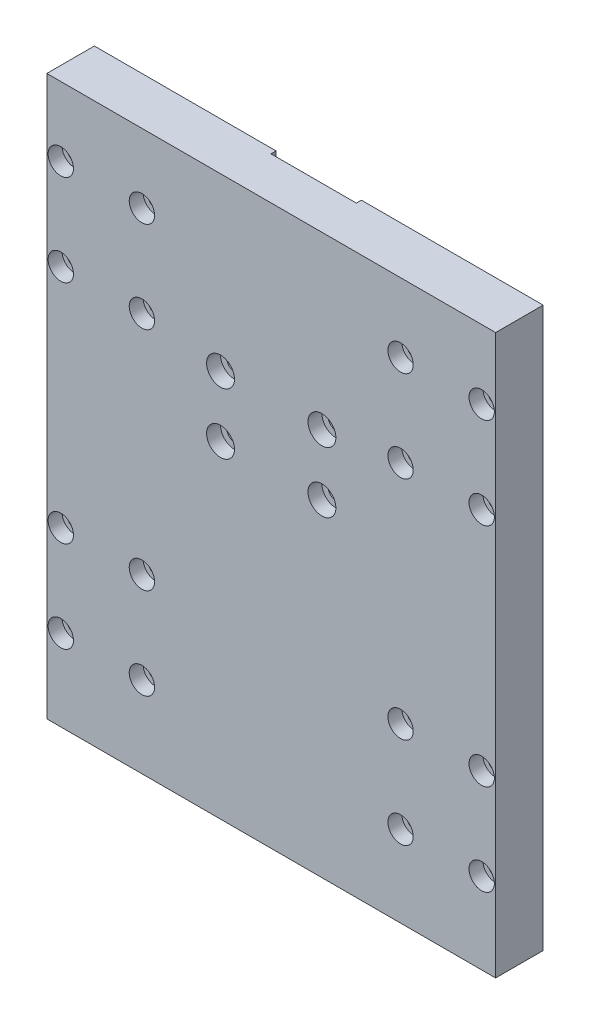
SolidWorks part; units mm, degrees
ref_plane "Front Plane" through (0, 0, 0) normal (0, 0, 1) x (1, 0, 0)
ref_plane "Top Plane" through (0, 0, 0) normal (0, 1, 0) x (1, 0, 0)
ref_plane "Right Plane" through (0, 0, 0) normal (1, 0, 0) x (0, 0, -1)
sketch "Sketch1" plane through (0, 0, 0) normal (0, 0, 1) x (1, 0, 0)
  line L0 (88.5186, 66.4333) -> (-88.5186, 66.4333)
  line L1 (88.5186, 46.4333) -> (88.5186, -4.0667)
  line L3 (88.5186, 46.4333) -> (88.5186, 66.4333)
  line L4 (88.5186, -4.0667) -> (88.5186, -154.0667)
  line L5 (-88.5186, -4.0667) -> (-88.5186, -154.0667)
  line L6 (-88.5186, 46.4333) -> (-88.5186, 66.4333)
  line L7 (-88.5186, 46.4333) -> (-88.5186, -4.0667)
  line L8 (-88.5186, -154.0667) -> (88.5186, -154.0667)
  circle A0 centre (83.0186, 39.1833) radius 3
  circle A1 centre (51.0186, 39.1833) radius 3
  circle A2 centre (83.0186, 3.1833) radius 3
  circle A3 centre (51.0186, 3.1833) radius 3
  circle A4 centre (83.0186, -86.0167) radius 3
  circle A5 centre (51.0186, -86.0167) radius 3
  circle A6 centre (51.0186, -122.0167) radius 3
  circle A7 centre (83.0186, -122.0167) radius 3
  circle A8 centre (-83.0186, -122.0167) radius 3
  circle A9 centre (-51.0186, -122.0167) radius 3
  circle A10 centre (-51.0186, -86.0167) radius 3
  circle A11 centre (-83.0186, -86.0167) radius 3
  circle A12 centre (-51.0186, 3.1833) radius 3
  circle A13 centre (-83.0186, 3.1833) radius 3
  circle A14 centre (-51.0186, 39.1833) radius 3
  circle A15 centre (-83.0186, 39.1833) radius 3
  point P5 (0, 0)
  point P6 (0, 0)
  point P7 (0, 0)
  point P9 (0, 0)
  point P44 (0, 0)
extrude "Boss-Extrude1" add sketch "Sketch1" along normal blind 18.75
sketch "Sketch2" plane through (0, 0, 18.75) normal (0, 0, 1) x (1, 0, 0)
  circle A1 centre (-51.0186, 39.1833) radius 5
  circle A2 centre (-83.0186, 39.1833) radius 5
  circle A3 centre (-83.0186, 3.1833) radius 5
  circle A4 centre (51.0186, 39.1833) radius 5
  circle A5 centre (83.0186, 39.1833) radius 5
  circle A6 centre (83.0186, 3.1833) radius 5
  circle A7 centre (51.0186, 3.1833) radius 5
  circle A8 centre (-51.0186, 3.1833) radius 5
  circle A9 centre (-83.0186, -86.0167) radius 5
  circle A10 centre (-51.0186, -86.0167) radius 5
  circle A11 centre (-51.0186, -122.0167) radius 5
  circle A12 centre (-83.0186, -122.0167) radius 5
  circle A13 centre (51.0186, -122.0167) radius 5
  circle A14 centre (51.0186, -86.0167) radius 5
  circle A15 centre (83.0186, -86.0167) radius 5
  circle A16 centre (83.0186, -122.0167) radius 5
extrude "Cut-Extrude3" cut sketch "Sketch2" against normal blind 5.5
sketch "Sketch4" plane through (0, 0, 18.75) normal (0, 0, 1) x (1, 0, 0)
  circle A0 centre (-20, -25) radius 3
  circle A1 centre (20, -25) radius 3
  circle A2 centre (20, -1) radius 3
  circle A3 centre (-20, -1) radius 3
  dimension "D1" = 2
  dimension "D2" = 2
hole_wizard "CBORE for M5 Hex Head Bolt1" positions "Sketch5" profile "Sketch6" counterbore size "M5" standard "ISO" end condition through all
sketch "Sketch5" plane through (0, 0, 18.75) normal (0, 0, 1) x (1, 0, 0)
  point P0 (-20, -1)
  point P3 (20, -1)
  point P6 (-20, -25)
  point P9 (20, -25)
sketch "Sketch6" plane through (-20, -1, 18.75) normal (1, 0, 0) x (0, -1, 0)
  line L0 (0, 0) -> (0, 18.75)
  line L1 (0, 18.75) -> (3, 18.75)
  line L3 (3, 18.75) -> (3, 5.5)
  line L4 (3, 5.5) -> (5.5, 5.5)
  line L5 (5.5, 5.5) -> (5.5, 0)
  line L7 (5.5, 0) -> (0, 0)
  line L11 (0, -6.35) -> (0, 107.95) construction
  dimension "Thru Hole Dia." = 6
  dimension "Thru Hole Depth" = 18.75
  dimension "C'Bore Dia." = 11
  dimension "C'Bore Depth" = 5.5
sketch "Sketch7" plane through (0, 66.4333, 0) normal (0, 1, 0) x (1, 0, 0)
  line L5 (-14.8284, -2) -> (-16.8284, -2)
  line L6 (-16.8284, -2) -> (-16.8284, 0)
  line L10 (14.8284, -2) -> (16.8284, -2)
  line L12 (-14.8284, -2) -> (14.8284, -2)
  line L14 (16.8284, -2) -> (16.8284, 0)
  line L15 (16.8284, 0) -> (-16.8284, 0)
extrude "Cut-Extrude4" cut sketch "Sketch7" against normal blind 40
sketch "Sketch8" plane through (0, 0, 0) normal (0, 0, -1) x (-1, 0, 0)
  line L0 (18.9411, 17.5285) -> (18.9411, 6.4715)
  line L1 (16.9411, 16.5) -> (16.9411, 7.5)
  line L2 (-16.9411, 7.5) -> (-16.9411, 16.5)
  line L3 (-18.9411, 6.4715) -> (-18.9411, 17.5285)
  line L4 (-17.3614, 5.3543) -> (17.3614, 5.3543)
  line L5 (-17.3614, 18.6457) -> (17.3614, 18.6457)
  arc A0 (18.9411, 17.5285) -> (17.3614, 18.6457) centre (-31.5511, -52.1871) ccw
  arc A1 (-16.225, 17) -> (-16.9411, 16.5) centre (31.551, -52.1869) ccw
  arc A2 (16.9411, 16.5) -> (16.225, 17) centre (-31.5511, -52.1871) ccw
  arc A3 (16.225, 7) -> (16.9411, 7.5) centre (-31.551, 76.1869) ccw
  arc A4 (-16.9411, 7.5) -> (-16.225, 7) centre (31.5511, 76.1871) ccw
  arc A5 (17.3614, 5.3543) -> (18.9411, 6.4715) centre (-31.551, 76.1869) ccw
  arc A6 (-18.9411, 6.4715) -> (-17.3614, 5.3543) centre (31.5511, 76.1871) ccw
  arc A7 (-17.3614, 18.6457) -> (-18.9411, 17.5285) centre (31.551, -52.1869) ccw
  dimension "D1" = 2
extrude "Cut-Extrude5" cut sketch "Sketch8" against normal blind 4
